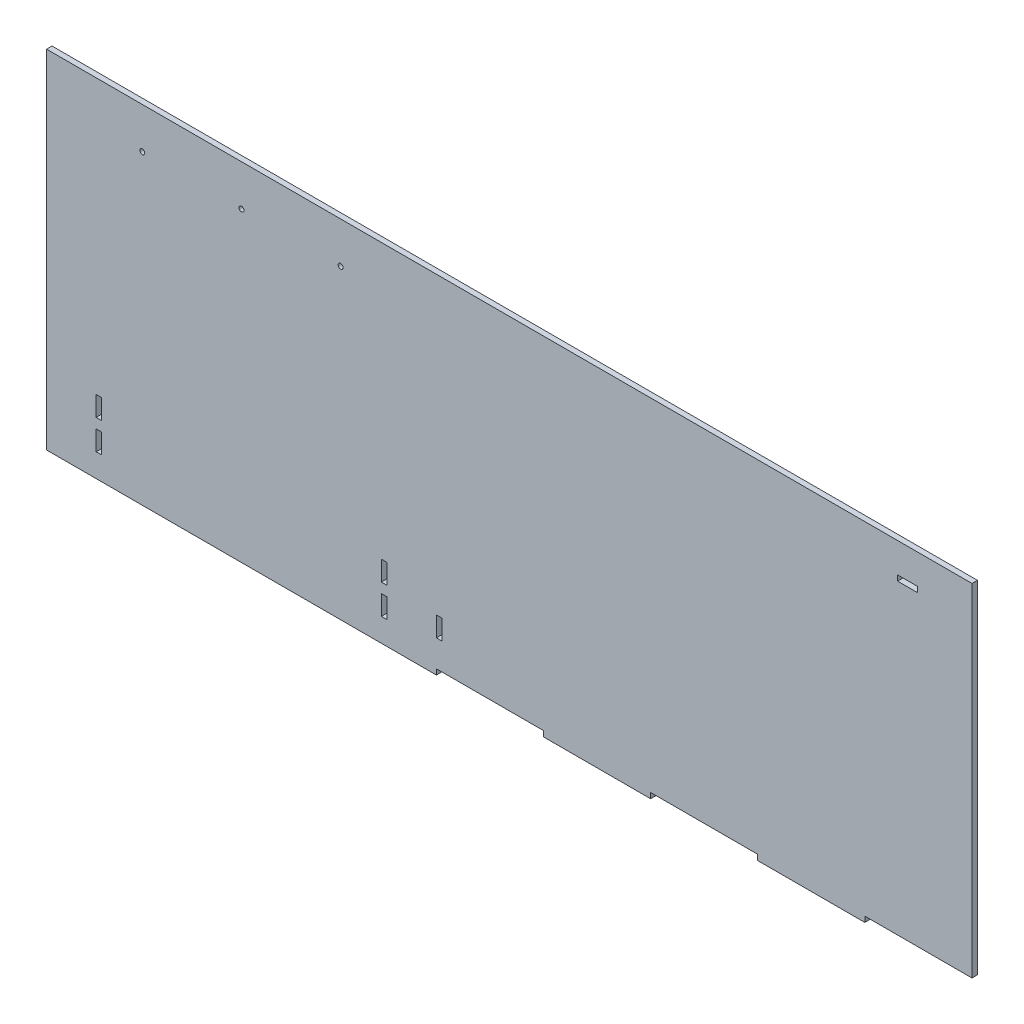
SolidWorks part; units mm, degrees
ref_plane "Alzado" through (0, 0, 0) normal (0, 0, 1) x (1, 0, 0)
ref_plane "Planta" through (0, 0, 0) normal (0, 1, 0) x (1, 0, 0)
ref_plane "Vista lateral" through (0, 0, 0) normal (1, 0, 0) x (0, 0, -1)
sketch "Croquis1" plane through (0, 0, 0) normal (0, 0, 1) x (1, 0, 0)
  line L0 (-236.122, 20.4075) -> (-241.622, 20.4075)
  line L1 (-241.622, 0.4075) -> (-236.122, 0.4075)
  line L2 (-241.622, 5.6305) -> (-291.622, 5.6305) construction
  line L3 (45.878, 0.4075) -> (51.378, 0.4075)
  line L4 (-291.622, -23.0714) -> (101.378, -23.0714)
  line L5 (-245.122, 296.4497) -> (509.668, 296.4497) construction
  line L6 (-236.122, 25.4075) -> (-256.3979, 25.4075) construction
  line L7 (101.378, 61.9286) -> (101.378, -23.0714) construction
  line L8 (101.378, 61.9286) -> (101.378, 160.9286) construction
  line L9 (-241.622, 20.4075) -> (-241.622, 0.4075)
  line L10 (-236.122, 0.4075) -> (-236.122, 20.4075)
  line L11 (511.378, 187.5745) -> (641.378, 187.5745) construction
  line L12 (-236.122, 20.4075) -> (-236.122, 30.4075) construction
  line L13 (-236.122, 30.4075) -> (-236.122, 50.4075)
  line L14 (-241.622, 30.4075) -> (-236.122, 30.4075)
  line L15 (101.378, 160.9286) -> (201.378, 160.9286) construction
  line L16 (45.878, 20.4075) -> (51.378, 20.4075)
  line L17 (-245.122, 285.6275) -> (-195.122, 285.6275) construction
  line L18 (-245.122, 285.6275) -> (4.878, 285.6275) construction
  line L19 (-245.122, 50.4075) -> (54.878, 50.4075) construction
  line L20 (54.878, 50.4075) -> (54.878, 0.4075) construction
  line L21 (51.378, 20.4075) -> (51.378, 0.4075)
  line L22 (45.878, 30.4075) -> (51.378, 30.4075)
  line L23 (51.378, 30.4075) -> (51.378, 50.4075)
  line L24 (45.878, 50.4075) -> (45.878, 30.4075)
  line L25 (51.378, 50.4075) -> (45.878, 50.4075)
  line L26 (-291.622, -23.0714) -> (-291.622, 326.9286)
  line L27 (201.378, 180.9095) -> (201.378, 160.9286) construction
  line L28 (45.878, 0.4075) -> (45.878, 20.4075)
  line L29 (101.378, 61.9286) -> (203.878, 61.9286) construction
  line L30 (101.378, 296.9286) -> (101.378, 326.9286) construction
  line L31 (-291.622, 326.9286) -> (641.378, 326.9286)
  line L32 (641.378, 326.9286) -> (641.378, -17.5714)
  line L33 (576.378, 296.9286) -> (566.378, 296.9286)
  line L34 (-245.122, 296.4497) -> (54.878, 296.4497) construction
  line L35 (533.378, -17.5714) -> (641.378, -17.5714)
  line L36 (106.878, 9.4286) -> (101.378, 9.4286)
  line L37 (101.378, 296.9286) -> (101.378, 61.9286) construction
  line L38 (101.378, 296.9286) -> (511.378, 296.9286) construction
  line L39 (511.378, 296.9286) -> (511.378, 61.9286) construction
  line L40 (101.378, 61.9286) -> (511.378, 61.9286) construction
  line L41 (106.878, 29.4286) -> (106.878, 9.4286)
  line L42 (101.378, 9.4286) -> (101.378, 29.4286)
  line L43 (511.378, 61.9286) -> (408.878, 61.9286) construction
  line L44 (101.378, 29.4286) -> (106.878, 29.4286)
  line L45 (209.378, -17.5714) -> (209.378, -23.0714)
  line L46 (209.378, -23.0714) -> (317.378, -23.0714)
  line L47 (317.378, -23.0714) -> (317.378, -17.5714)
  line L48 (317.378, -17.5714) -> (425.378, -17.5714)
  line L49 (425.378, -17.5714) -> (425.378, -23.0714)
  line L50 (101.378, -23.0714) -> (101.378, -17.5714)
  line L51 (101.378, -17.5714) -> (209.378, -17.5714)
  line L52 (425.378, -23.0714) -> (533.378, -23.0714)
  line L53 (533.378, -23.0714) -> (533.378, -17.5714)
  line L54 (566.378, 296.9286) -> (566.378, 291.4286)
  line L55 (566.378, 291.4286) -> (586.378, 291.4286)
  line L56 (586.378, 291.4286) -> (586.378, 296.9286)
  line L57 (586.378, 296.9286) -> (576.378, 296.9286)
  line L58 (-256.3979, 25.4075) -> (-256.3979, 285.6275) construction
  line L59 (-195.122, 285.6275) -> (-95.122, 285.6275) construction
  line L69 (101.378, 19.4286) -> (112.7976, 19.4286) construction
  line L70 (23.166, 160.9286) -> (-19.2447, 160.9286) construction
  line L71 (-236.122, 50.4075) -> (-241.622, 50.4075)
  line L72 (-241.622, 50.4075) -> (-241.622, 30.4075)
  line L73 (23.166, 310.9286) -> (23.166, 10.9286) construction
  circle A0 centre (-195.122, 285.6275) radius 2.5
  circle A1 centre (-95.122, 285.6275) radius 2.5
  circle A2 centre (4.878, 285.6275) radius 2.5
  dimension "D1" = 540
extrude "Saliente-Extruir2" add sketch "Croquis1" along normal blind 5.5
sketch "Croquis2" plane through (0, 0, 5.5) normal (0, 0, 1) x (1, 0, 0)
